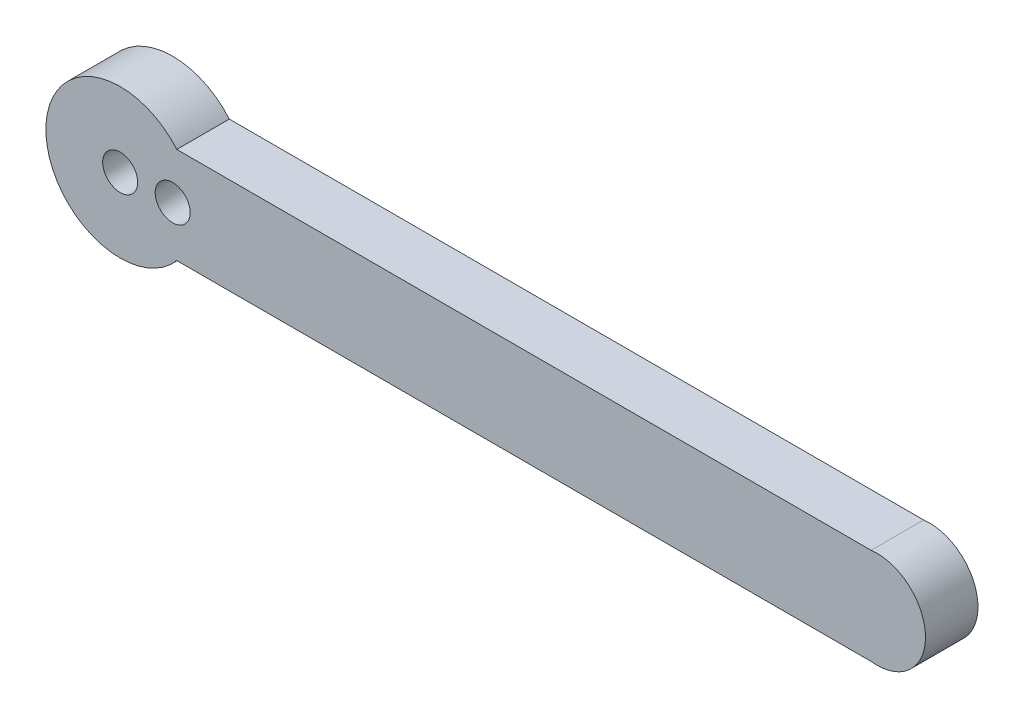
SolidWorks part; units mm, degrees
ref_plane "Front Plane" through (0, 0, 0) normal (0, 0, 1) x (1, 0, 0)
ref_plane "Top Plane" through (0, 0, 0) normal (0, 1, 0) x (1, 0, 0)
ref_plane "Right Plane" through (0, 0, 0) normal (1, 0, 0) x (0, 0, -1)
sketch "Sketch1" plane through (0, 0, 0) normal (0, 0, 1) x (1, 0, 0)
  line L0 (42.6509, 2.7085) -> (43.2346, 2.75) construction
  line L1 (3.2346, 2.75) -> (43.2346, 2.75)
  line L3 (3.2346, -2.75) -> (43.2346, -2.75)
  line L4 (43.2346, 2.75) -> (43.2346, -2.75)
  line L7 (42.6509, -2.7085) -> (43.2346, -2.75) construction
  circle A0 centre (0, 0) radius 4.2456
  circle A1 centre (43.2346, 0) radius 2.7706
  dimension "D1" = 5.5
  dimension "D2" = 40
extrude "Boss-Extrude1" add sketch "Sketch1" along normal blind 3 contours A1 L1 A0 L3 | L3 A1 L1 L4 | L1 A1 L3 L4
sketch "Sketch2" plane through (0, 0, 3) normal (0, 0, 1) x (1, 0, 0)
  line L0 (0, 0) -> (3, 0) construction
  circle A0 centre (0, 0) radius 1
  circle A1 centre (3, 0) radius 1
  dimension "D1" = 3
extrude "Cut-Extrude1" cut sketch "Sketch2" against normal blind 10
